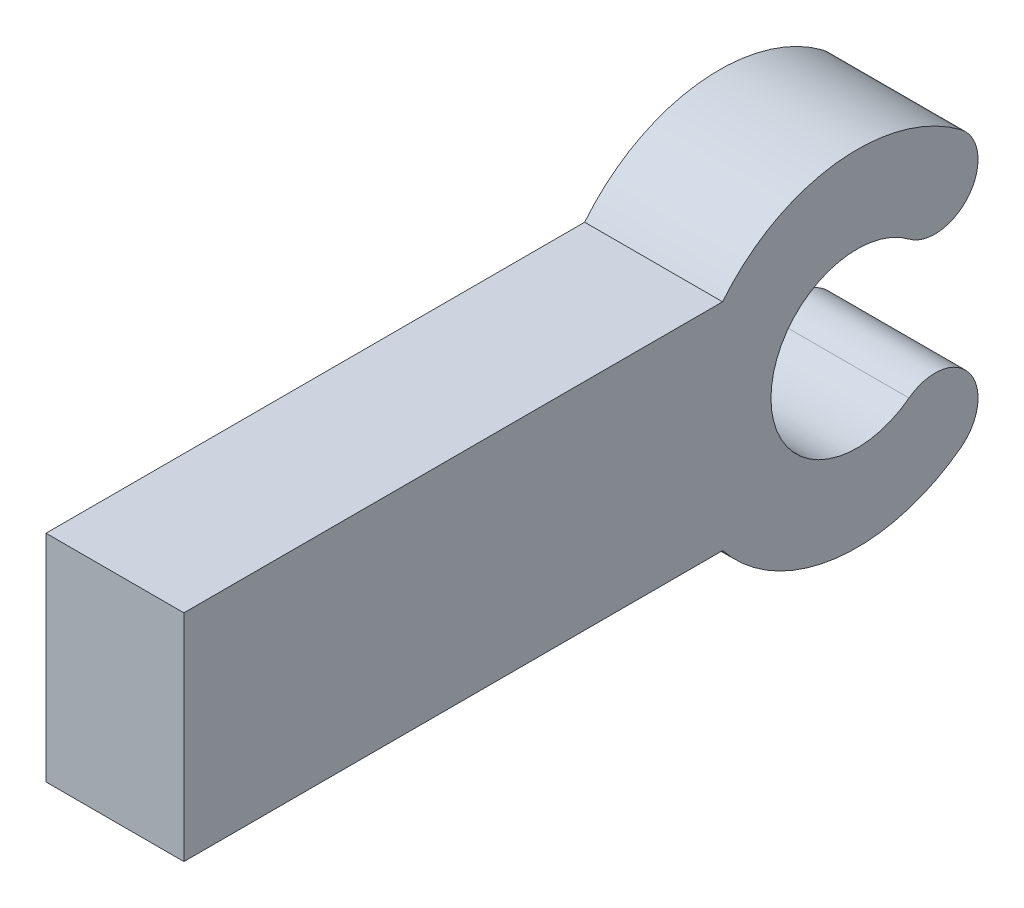
SolidWorks part; units mm, degrees
material "Delrin 2700 NC010, Low Viscosity Acetal Copolymer (SS)"
ref_plane "Front Plane" through (0, 0, 0) normal (0, 0, 1) x (1, 0, 0)
ref_plane "Top Plane" through (0, 0, 0) normal (0, 1, 0) x (1, 0, 0)
ref_plane "Right Plane" through (0, 0, 0) normal (1, 0, 0) x (0, 0, -1)
sketch "Sketch1" plane through (0, 0, 0) normal (1, 0, 0) x (0, 0, -1)
  line L0 (0, 1.27) -> (10.4547, 1.27) construction
  line L1 (0, 0) -> (6.35, 0)
  line L2 (0, 0) -> (0, 2.54)
  line L3 (0, 2.54) -> (6.35, 2.54)
  line L4 (7.9362, 1.27) -> (9.1591, 2.8928) construction
  line L5 (7.9362, 1.27) -> (9.1591, -0.3528) construction
  arc A0 (9.1591, 2.8928) -> (6.35, 2.54) centre (7.9362, 1.27) ccw
  arc A1 (8.5477, 2.0814) -> (8.5477, 0.4586) centre (7.9362, 1.27) ccw
  arc A2 (9.1591, 2.8928) -> (8.5477, 2.0814) centre (8.8534, 2.4871) cw
  arc A3 (8.5477, 0.4586) -> (9.1591, -0.3528) centre (8.8534, 0.0529) cw
  arc A4 (6.35, 0) -> (9.1591, -0.3528) centre (7.9362, 1.27) ccw
  dimension "D3" = 2.032
  dimension "D4" = 4.064
  dimension "D1" = 2.54
  dimension "D2" = 6.35
  dimension "D5" = 53
extrude "Boss-Extrude1" add sketch "Sketch1" along normal blind 1.6256
